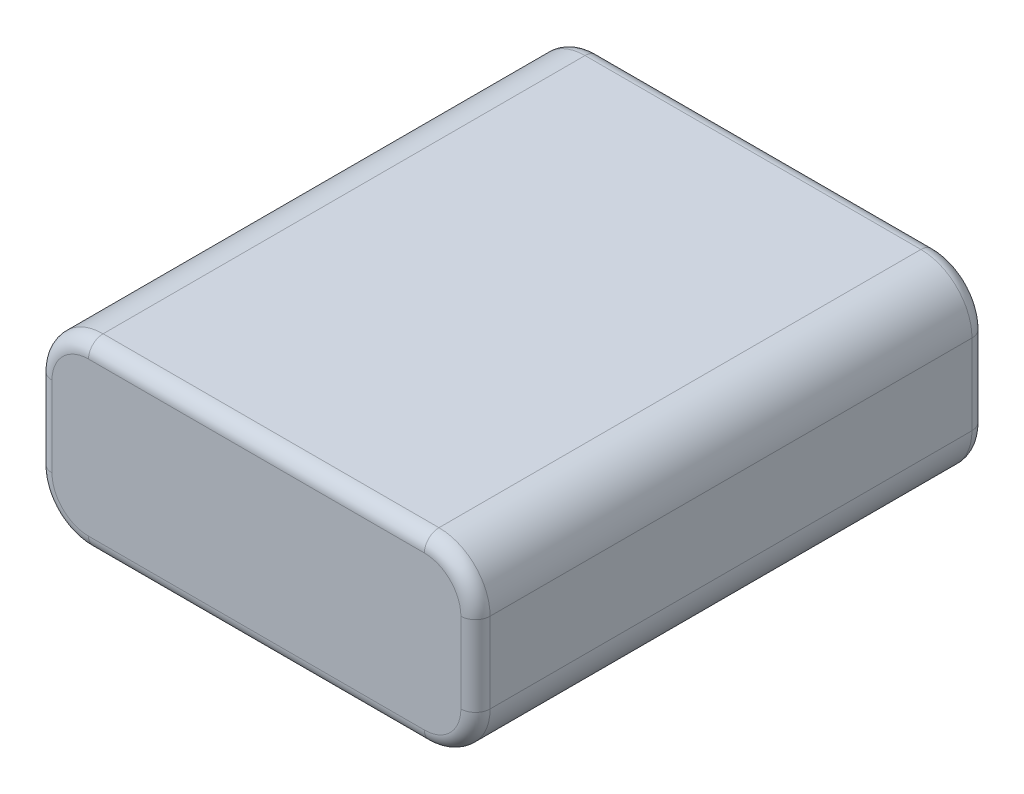
SolidWorks part; units mm, degrees
ref_plane "Front Plane" through (0, 0, 0) normal (0, 0, 1) x (1, 0, 0)
ref_plane "Top Plane" through (0, 0, 0) normal (0, 1, 0) x (1, 0, 0)
ref_plane "Right Plane" through (0, 0, 0) normal (1, 0, 0) x (0, 0, -1)
sketch "Sketch1" plane through (0, 0, 0) normal (0, 0, 1) x (1, 0, 0)
  line L1 (7, 0) -> (53, 0)
  line L2 (0, 7) -> (0, 18)
  line L3 (7, 25) -> (53, 25)
  line L4 (60, 7) -> (60, 18)
  arc A0 (53, 25) -> (60, 18) centre (53, 18) cw
  arc A1 (53, 0) -> (60, 7) centre (53, 7) ccw
  arc A2 (7, 0) -> (0, 7) centre (7, 7) cw
  arc A3 (0, 18) -> (7, 25) centre (7, 18) cw
  point P7 (60, 25)
  point P12 (0, 0)
  point P15 (0, 25)
  dimension "D3" = 7
  dimension "D1" = 25
  dimension "D2" = 60
extrude "Boss-Extrude1" add sketch "Sketch1" along normal blind 70
fillet "Fillet1" radius 2 16 edges at (30, 25, 0) (2.0503, 22.9497, 0) (0, 12.5, 0) (2.0503, 2.0503, 0) (30, 0, 0) (57.9497, 2.0503, 0) (60, 12.5, 0) (57.9497, 22.9497, 0) (60, 12.5, 70) (57.9497, 2.0503, 70) (30, 0, 70) (2.0503, 2.0503, 70) (0, 12.5, 70) (2.0503, 22.9497, 70) (30, 25, 70) (57.9497, 22.9497, 70)
